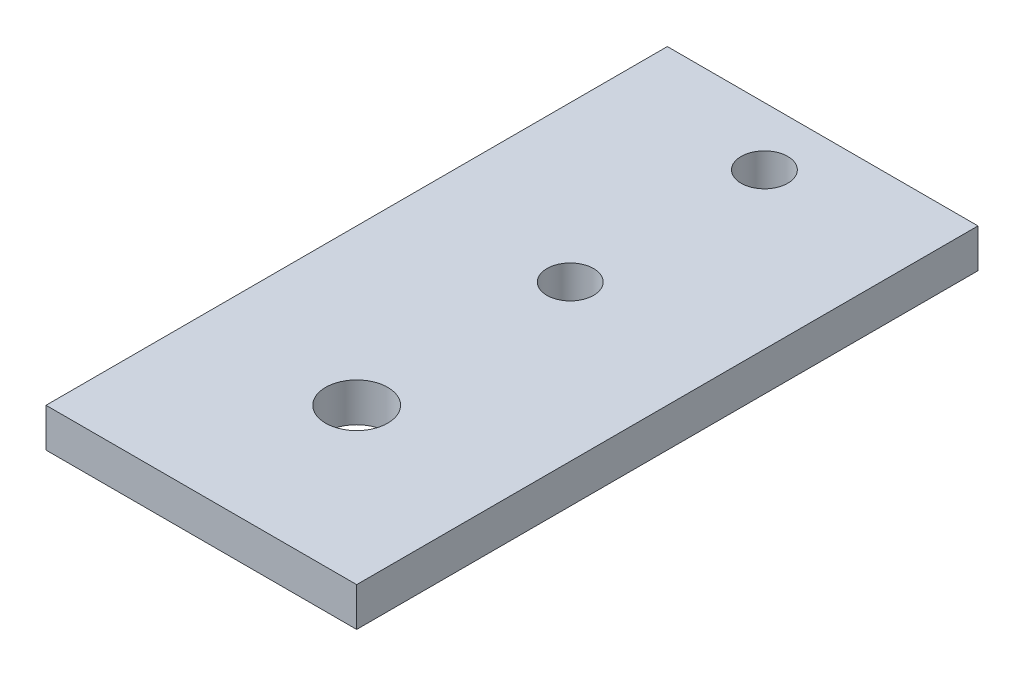
SolidWorks part; units mm, degrees
ref_plane "Front Plane" through (0, 0, 0) normal (0, 0, 1) x (1, 0, 0)
ref_plane "Top Plane" through (0, 0, 0) normal (0, 1, 0) x (1, 0, 0)
ref_plane "Right Plane" through (0, 0, 0) normal (1, 0, 0) x (0, 0, -1)
sketch "Sketch1" plane through (0, 0, 0) normal (0, 1, 0) x (1, 0, 0)
  line L0 (20, 0) -> (20, 80) construction
  line L1 (0, 0) -> (40, 0)
  line L2 (0, 0) -> (0, 80)
  line L3 (0, 80) -> (40, 80)
  line L4 (40, 0) -> (40, 80)
  circle A0 centre (20, 72.5) radius 3
  circle A1 centre (20, 47.5) radius 3
  circle A2 centre (20, 20) radius 4
  dimension "D5" = 8
  dimension "D6" = 6
  dimension "D7" = 6
  dimension "D1" = 40
  dimension "D2" = 80
  dimension "D3" = 20
  dimension "D4" = 25
  dimension "D8" = 7.5
extrude "Boss-Extrude1" add sketch "Sketch1" along normal blind 5
equation "\"a\"= \"Beam Profile@Plasma Beta.Assembly\"'Beam profile"
equation "\"D3@Sketch1\"=\"a\"/2"
equation "\"D2@Sketch1\"=\"a\"+40"
